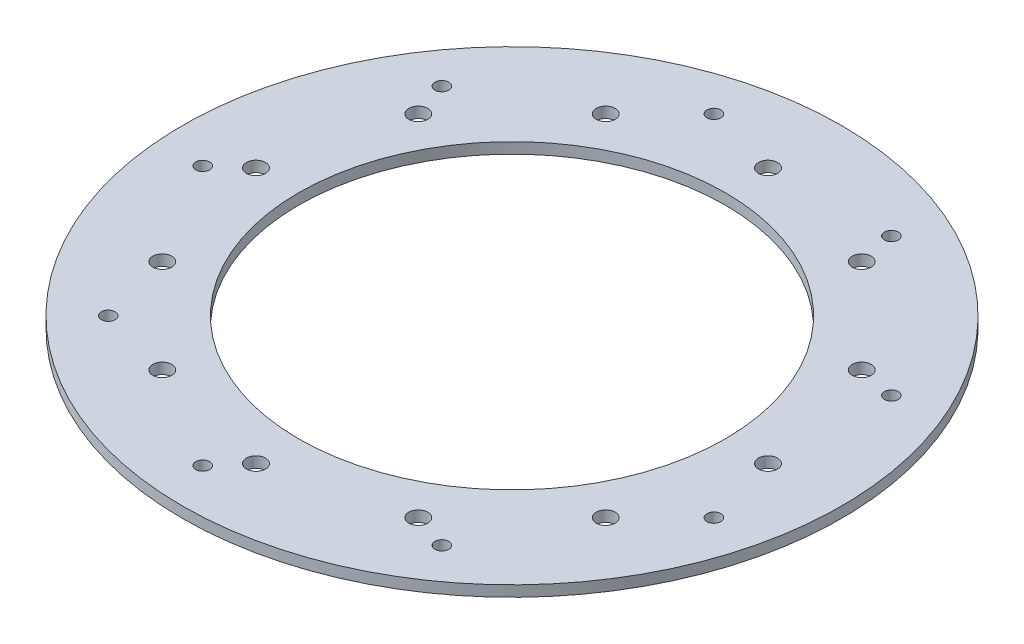
SolidWorks part; units mm, degrees
material "1060 Alloy"
ref_plane "Ebene vorne" through (0, 0, 0) normal (0, 0, 1) x (1, 0, 0)
ref_plane "Ebene oben" through (0, 0, 0) normal (0, 1, 0) x (1, 0, 0)
ref_plane "Ebene rechts" through (0, 0, 0) normal (1, 0, 0) x (0, 0, -1)
sketch "Sketch1" plane through (0, 0, 0) normal (0, 1, 0) x (1, 0, 0)
  circle A0 centre (0, 0) radius 49.3
  circle A1 centre (0, 0) radius 76.182
  dimension "D1" = 152.364
  dimension "D2" = 98.6
extrude "Boss-Extrude1" add sketch "Sketch1" along normal blind 2.5
sketch "Sketch2" plane through (0, 2.5, 0) normal (0, 1, 0) x (1, 0, 0)
  line L0 (0, 0) -> (-65.7489, -5.7523) construction
  line L1 (0, 0) -> (-20, 0) construction
  circle A0 centre (-65.7489, -5.7523) radius 1.6
  point P21 (0, 4)
  point P28 (0, 0)
  dimension "D1" = 3.2
  dimension "D2" = 20
  dimension "D3" = 66
  dimension "D4" = 5
extrude "Cut-Extrude1" cut sketch "Sketch2" against normal through all
sketch "Sketch3" plane through (0, 2.5, 0) normal (0, 1, 0) x (1, 0, 0)
  circle A0 centre (0, 59.18) radius 2.2
  circle A1 centre (29.59, 51.2514) radius 2.2
  circle A2 centre (51.2514, 29.59) radius 2.2
  circle A3 centre (59.18, 0) radius 2.2
  circle A4 centre (51.2514, -29.59) radius 2.2
  circle A5 centre (29.59, -51.2514) radius 2.2
  circle A6 centre (0, -59.18) radius 2.2
  circle A7 centre (-29.59, -51.2514) radius 2.2
  circle A8 centre (-51.2514, -29.59) radius 2.2
  circle A9 centre (-59.18, 0) radius 2.2
  circle A10 centre (-51.2514, 29.59) radius 2.2
  circle A11 centre (-29.59, 51.2514) radius 2.2
  point P28 (0, 0)
  dimension "D1" = 4.4
  dimension "D3" = 118.36
  dimension "D2" = 12
extrude "Cut-Extrude2" cut sketch "Sketch3" against normal through all
pattern_circular "CirPattern1" count 9 over 360 about axis through (0, 0, 0) along (0, 1, 0) of "Cut-Extrude1"
equation "\"d_i_tube\"= 150mm'Inner Rocket Body Composite Tube Diameter"
equation "\"t_tube\"= 1.182mm'Thickness of Rocket Body Composite Tube"
equation "\"l_upper_body_tube\"= 949.3mm'Upper Rocket Body Composite Tube length"
equation "\"l_lower_body_tube\"= 816mm'Lower Rocket Body Composite Tube Length"
equation "\"d_a_NC\"= 154mm'Outer Diameter of Nosecone base"
equation "\"d_i_phenolic_tube\"= 152.3mm'Inner Phenolic Tube Diameter"
equation "\"t_phenolic_tube\"= 2mm'Thickness of Phenolic Body Tube"
equation "\"l_fin_cut\"= 220mm'Length of fin on Motor Retainer"
equation "\"t_SW-Panel\"= 11.482mm'Thickness of Sandwich-Panel"
equation "\"l_motor_tube\"=610mm'Length of phenolic motor tube"
equation "\"d_i_motor_tube\"=99.06mm'Inner diameter of phenolic motor tube"
equation "\"t_motor_tube\"=1.58mm'Thicknes of phenolic motor tube"
equation "\"l_cut_fin_centering\"=13mm'Length of cut for fin alignement on fin centering rings"
equation "\"D1@Sketch1\"=\"d_i_tube\"+\"t_tube\"*2"
